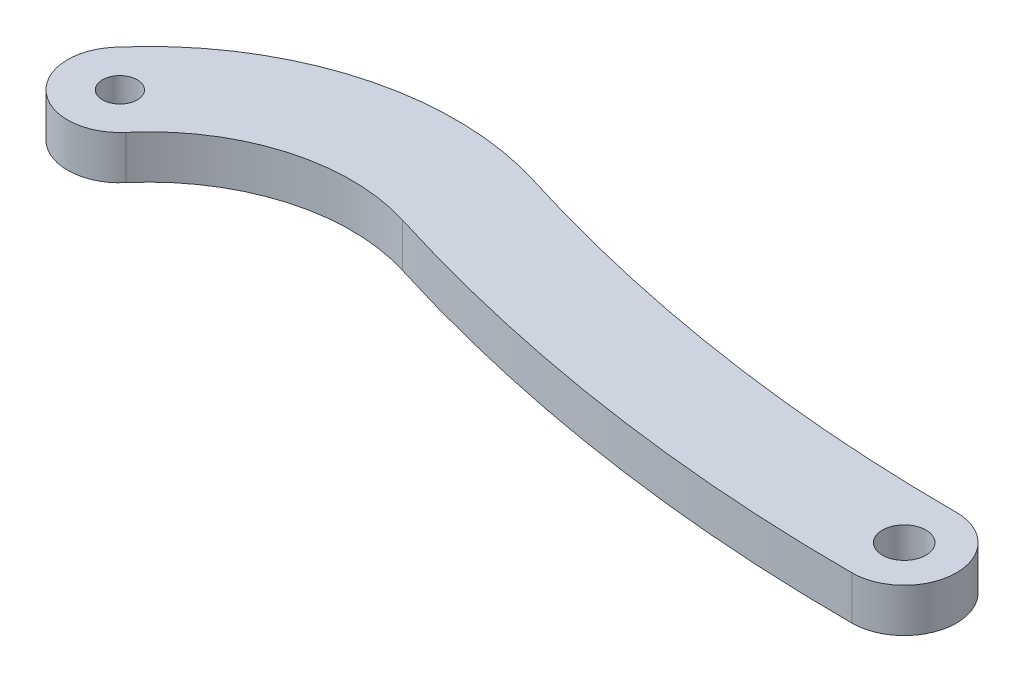
SolidWorks part; units mm, degrees
ref_plane "Front Plane" through (0, 0, 0) normal (0, 0, 1) x (1, 0, 0)
ref_plane "Top Plane" through (0, 0, 0) normal (0, 1, 0) x (1, 0, 0)
ref_plane "Right Plane" through (0, 0, 0) normal (1, 0, 0) x (0, 0, -1)
sketch "Sketch1" plane through (0, 0, 0) normal (0, 1, 0) x (1, 0, 0)
  line L0 (0, 0) -> (114.3, 0) construction
  circle A0 centre (0, 0) radius 2.54
  circle A1 centre (114.3, 0) radius 3.175
  arc A2 (5.8096, -4.9308) -> (-5.8096, 4.9308) centre (0, 0) cw
  arc A3 (114.3, -7.62) -> (114.3, 7.62) centre (114.3, 0) ccw
  arc A6 (114.3, 7.62) -> (41.6134, 18.6899) centre (114.3, 251.79) cw
  arc A8 (-5.8096, 4.9308) -> (41.6134, 18.6899) centre (28.2965, -24.0163) cw
  arc A9 (5.8096, -4.9308) -> (37.0766, 4.1409) centre (28.2965, -24.0163) cw
  arc A10 (37.0766, 4.1409) -> (114.3, -7.62) centre (114.3, 251.79) ccw
  point P10 (114.0006, -8.89)
  point P12 (57.15, 0)
  point P13 (52.1453, 1.7944)
  point P15 (0, 0)
  point P16 (19.5942, -1.3778)
  point P18 (53.2503, 2.8278)
  point P19 (37.0766, 4.1409)
  dimension "D2" = 6.35
  dimension "D3" = 5.08
  dimension "D5" = 7.62
  dimension "D1" = 114.3
extrude "Boss-Extrude1" add sketch "Sketch1" along normal blind 6.35
